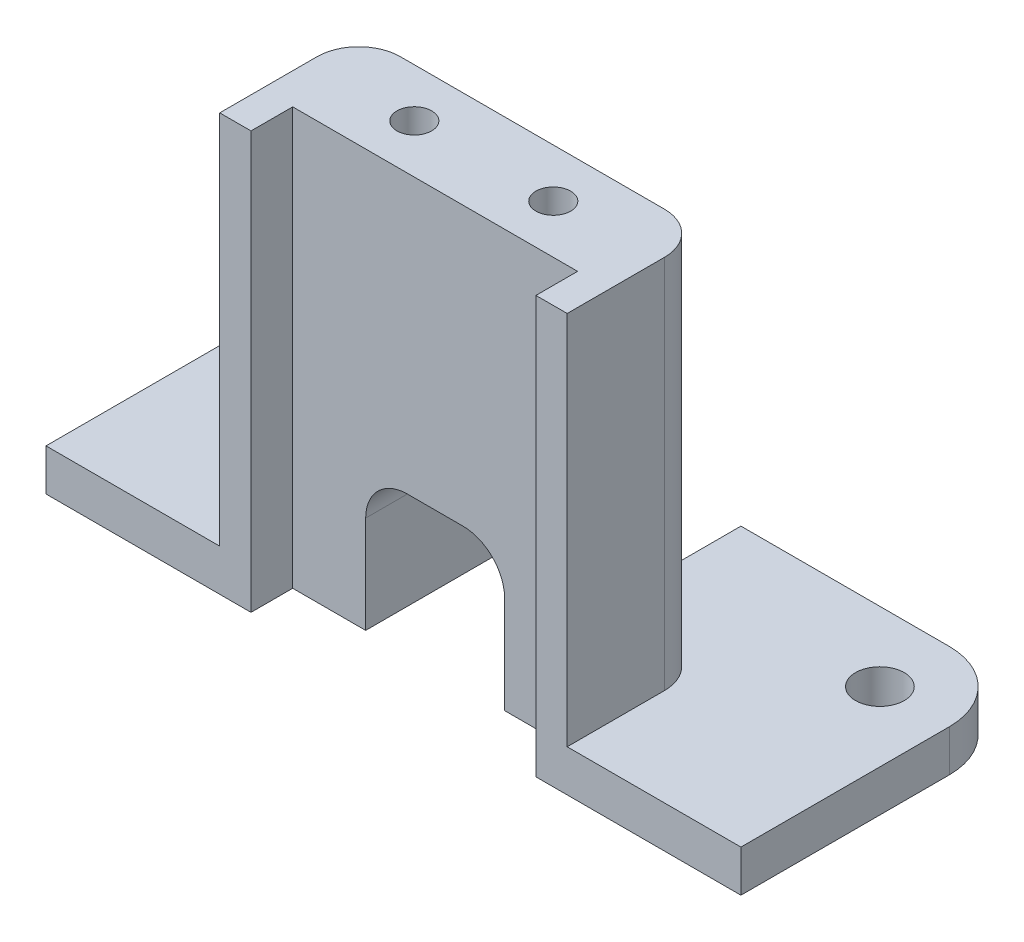
SolidWorks part; units mm, degrees
ref_plane "정면" through (0, 0, 0) normal (0, 0, 1) x (1, 0, 0)
ref_plane "윗면" through (0, 0, 0) normal (0, 1, 0) x (1, 0, 0)
ref_plane "우측면" through (0, 0, 0) normal (1, 0, 0) x (0, 0, -1)
sketch "스케치1" plane through (0, 0, 0) normal (0, 0, 1) x (1, 0, 0)
  line L1 (0, 0) -> (25, 0)
  line L2 (0, 0) -> (0, 30)
  line L3 (0, 30) -> (25, 30)
  line L4 (25, 0) -> (25, 30)
  dimension "D1" = 30
  dimension "D2" = 25
extrude "보스-돌출1" add sketch "스케치1" along normal blind 10
sketch "스케치2" plane through (0, 0, 10) normal (0, 0, 1) x (1, 0, 0)
  line L0 (25, 30) -> (0, 30) construction
  line L1 (2.25, 30) -> (22.75, 30)
  line L2 (2.25, 30) -> (2.25, 0)
  line L3 (2.25, 0) -> (22.75, 0)
  line L4 (22.75, 30) -> (22.75, 0)
  line L5 (0, 0) -> (25, 0) construction
  line L7 (0, 30) -> (0, 0) construction
  dimension "D1" = 20.5
  dimension "D2" = 2.25
extrude "컷-돌출1" cut sketch "스케치2" against normal blind 3
sketch "스케치3" plane through (0, 30, 0) normal (0, 1, 0) x (1, 0, 0)
  line L0 (7.5, -3.5) -> (17.5, -3.5) construction
  line L1 (25, 0) -> (0, 0) construction
  circle A0 centre (7.5, -3.5) radius 1.25
  circle A1 centre (17.5, -3.5) radius 1.25
  point P6 (12.5, 0)
  point P7 (12.5, -3.5)
  dimension "D2" = 10
  dimension "D3" = 2.5
  dimension "D1" = 3.5
extrude "컷-돌출2" cut sketch "스케치3" against normal blind 12
sketch "스케치5" plane through (0, 0, 0) normal (0, 0, -1) x (-1, 0, 0)
  line L0 (0, 0) -> (-25, 0) construction
  line L1 (-17.5, 0) -> (-7.5, 0)
  line L2 (-17.5, 0) -> (-17.5, 10)
  line L3 (-17.5, 10) -> (-7.5, 10)
  line L4 (-7.5, 0) -> (-7.5, 10)
  line L5 (0, 30) -> (0, 0) construction
  dimension "D1" = 10
  dimension "D2" = 10
  dimension "D3" = 7.5
extrude "컷-돌출4" cut sketch "스케치5" against normal blind 12
fillet "필렛1" radius 3 4 edges at (7.5, 10, 3.5) (17.5, 10, 3.5) (0, 15, 0) (25, 15, 0)
sketch "스케치6" plane through (0, 0, 0) normal (0, -1, 0) x (1, 0, 0)
  line L1 (7.5, 7) -> (2.25, 7)
  line L2 (7.5, 7) -> (7.5, -10)
  line L3 (7.5, -10) -> (-12.5, -10)
  line L4 (-12.5, 10) -> (-12.5, -10)
  line L5 (17.5, 7) -> (22.75, 7)
  line L6 (17.5, 7) -> (17.5, -10)
  line L7 (17.5, -10) -> (37.5, -10)
  line L8 (37.5, 10) -> (37.5, -10)
  line L9 (22.75, 10) -> (37.5, 10)
  line L10 (22.75, 10) -> (22.75, 7)
  line L11 (22.75, -10) -> (37.5, -10)
  line L13 (2.25, 10) -> (-12.5, 10)
  line L14 (2.25, 10) -> (2.25, 7)
  line L15 (-3.9768, -10) -> (-12.5, -10)
  line M14 (0, 10) -> (0, 3)
  arc M15 (0, 3) -> (3, 0) centre (3, 3) ccw
  line M16 (3, 0) -> (7.5, 0)
  dimension "D1" = 20
  dimension "D2" = 20
  dimension "D3" = 20
  dimension "D4" = 20
extrude "보스-돌출2" add sketch "스케치6" against normal blind 3 contours L9 L10 L5 L6 L7 L8 | L13 L4 L3 L2 M14 M16 M15
fillet "필렛2" radius 5 2 edges at (-12.5, 1.5, -10) (37.5, 1.5, -10)
sketch "스케치7" plane through (0, 3, 0) normal (0, 1, 0) x (1, 0, 0)
  circle A0 centre (32.5, 5) radius 1.75
  circle A1 centre (-7.5, 5) radius 1.75
  dimension "D1" = 3.5
extrude "컷-돌출5" cut sketch "스케치7" against normal blind 3
